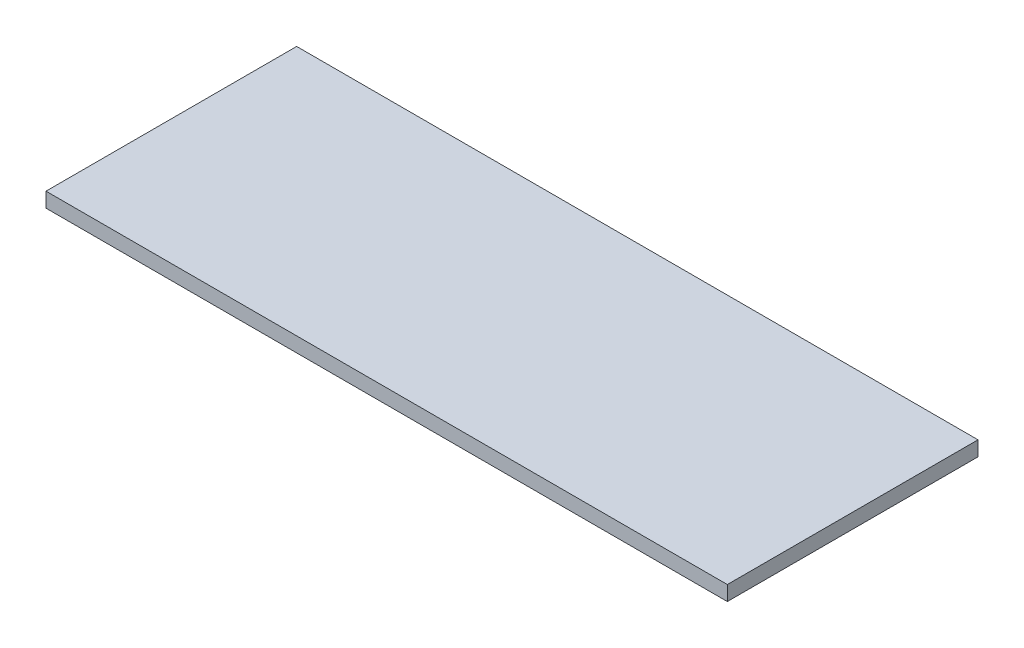
SolidWorks part; units mm, degrees
ref_plane "前视基准面" through (0, 0, 0) normal (0, 0, 1) x (1, 0, 0)
ref_plane "上视基准面" through (0, 0, 0) normal (0, 1, 0) x (1, 0, 0)
ref_plane "右视基准面" through (0, 0, 0) normal (1, 0, 0) x (0, 0, -1)
sketch "草图1" plane through (0, 0, 0) normal (0, 1, 0) x (1, 0, 0)
  line L4 (-0.9049, 134.96) -> (368.284, 134.96)
  line L5 (368.284, 134.96) -> (368.284, -0.865)
  line L6 (368.284, -0.865) -> (-0.9049, -0.865)
  line L7 (-0.9049, -0.865) -> (-0.9049, 134.96)
extrude "凸台-拉伸1" add sketch "草图1" along normal blind 8
sketch "草图3" plane through (0, 0, 0) normal (0, -1, 0) x (1, 0, 0)
  line L0 (-0.9049, 0.865) -> (368.284, 0.865) construction
  line L1 (64.0951, -22.135) -> (82.0951, -22.135)
  line L2 (64.0951, -22.135) -> (64.0951, -73.135)
  line L3 (64.0951, -73.135) -> (82.0951, -73.135)
  line L4 (82.0951, -22.135) -> (82.0951, -73.135)
  line L5 (-0.9049, -134.96) -> (-0.9049, 0.865) construction
  dimension "D1" = 18
  dimension "D2" = 51
  dimension "D3" = 23
  dimension "D4" = 65
extrude "凸台-拉伸3" add sketch "草图3" along normal blind 4
